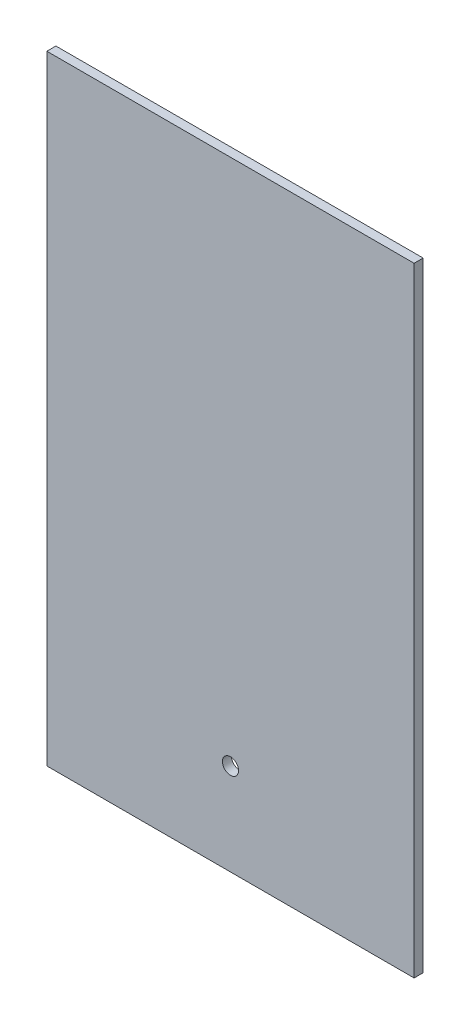
SolidWorks part; units mm, degrees
ref_plane "Plano frontal" through (0, 0, 0) normal (1, 0, 0) x (0, 1, 0)
ref_plane "Plano superior" through (0, 0, 0) normal (0, 0, 1) x (0, 1, 0)
ref_plane "Plano direito" through (0, 0, 0) normal (0, 1, 0) x (-1, 0, 0)
sketch "Esboço1" plane through (0, 0, 0) normal (0, 0, 1) x (0, 1, 0)
  line L1 (95.9, -56.9) -> (-95.9, -56.9)
  line L2 (95.9, -56.9) -> (95.9, 56.9)
  line L3 (95.9, 56.9) -> (-95.9, 56.9)
  line L4 (-95.9, -56.9) -> (-95.9, 56.9)
  line L5 (95.9, -56.9) -> (-95.9, 56.9) construction
  line L6 (95.9, 56.9) -> (-95.9, -56.9) construction
  point P0 (0, 0)
  dimension "D1" = 191.8
  dimension "D2" = 113.8
extrude "Ressalto-extrusão1" add sketch "Esboço1" along normal mid plane 2.8
sketch "Esboço2" plane through (0, 0, 1.4) normal (0, 0, 1) x (1, 0, 0)
  circle A0 centre (0, -67.4681) radius 2.5
  dimension "D1" = 5
extrude "Corte-extrusão1" cut sketch "Esboço2" against normal blind 2.8
